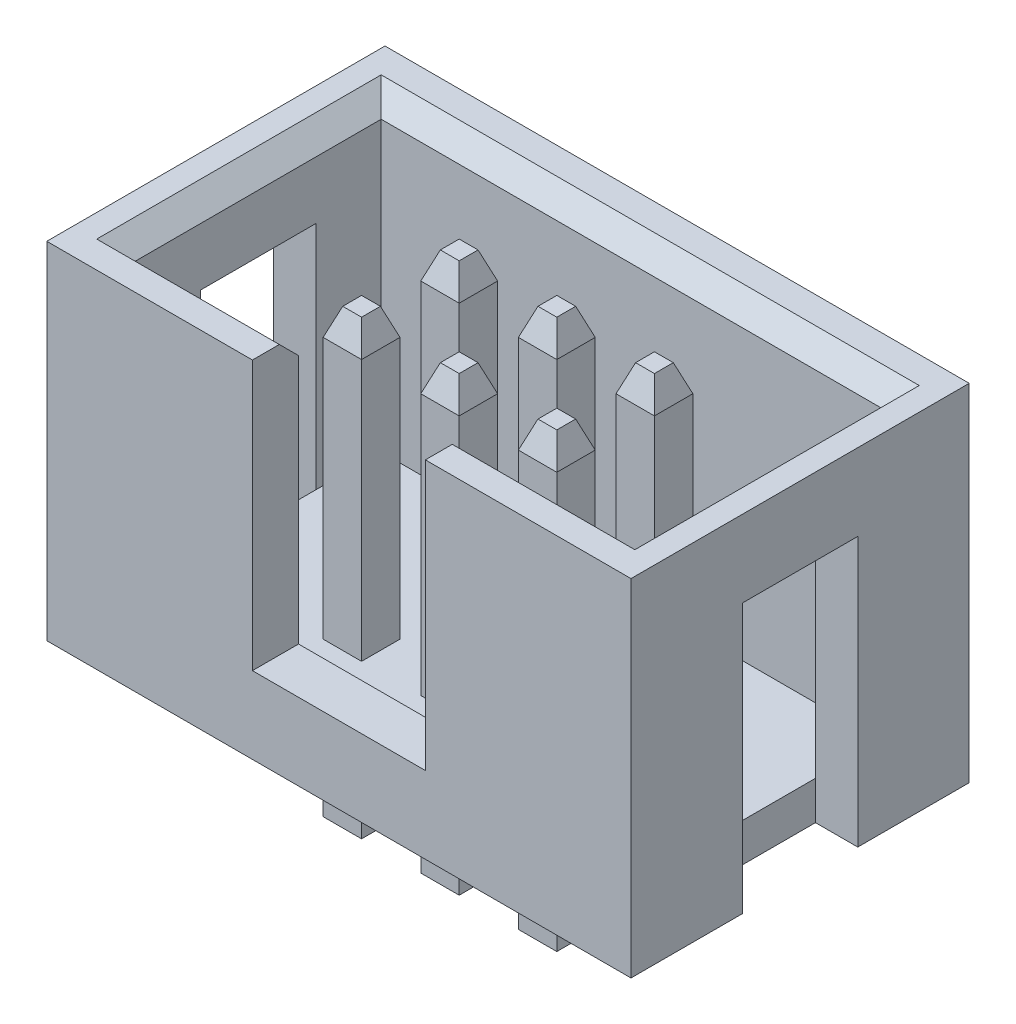
SolidWorks part; units mm, degrees
ref_plane "Front" through (0, 0, 0) normal (0, 0, 1) x (1, 0, 0)
ref_plane "Top" through (0, 0, 0) normal (0, 1, 0) x (1, 0, 0)
ref_plane "Right" through (0, 0, 0) normal (1, 0, 0) x (0, 0, -1)
sketch "Sketch1" plane through (0, 0, 0) normal (0, 1, 0) x (1, 0, 0)
  line L1 (0, 0) -> (15.2, 0)
  line L2 (0, 0) -> (0, 8.8)
  line L3 (0, 8.8) -> (15.2, 8.8)
  line L4 (15.2, 0) -> (15.2, 8.8)
  dimension "D1" = 15.2
  dimension "D2" = 8.8
extrude "Boss-Extrude1" add sketch "Sketch1" along normal blind 9
sketch "Sketch3" plane through (0, 9, 0) normal (0, 1, 0) x (1, 0, 0)
  line L0 (15.2, 8.8) -> (0, 8.8) construction
  line L1 (1.1, 7.6) -> (14.1, 7.6)
  line L2 (1.1, 7.6) -> (1.1, 1.2)
  line L3 (1.1, 1.2) -> (14.1, 1.2)
  line L4 (14.1, 7.6) -> (14.1, 1.2)
  line L5 (0, 8.8) -> (0, 0) construction
  dimension "D1" = 13
  dimension "D2" = 6.4
  dimension "D3" = 1.2
  dimension "D4" = 1.1
extrude "Cut-Extrude1" cut sketch "Sketch3" against normal blind 8
sketch "Sketch4" plane through (0, 9, 0) normal (0, 1, 0) x (1, 0, 0)
  line L0 (1.1, 1.2) -> (14.1, 1.2) construction
  line L1 (5.35, 1.2) -> (9.85, 1.2)
  line L2 (5.35, 1.2) -> (5.35, 0)
  line L3 (5.35, 0) -> (9.85, 0)
  line L4 (9.85, 1.2) -> (9.85, 0)
  line L5 (0, 0) -> (15.2, 0) construction
  line L6 (0, 8.8) -> (0, 0) construction
  dimension "D1" = 4.5
  dimension "D2" = 5.35
extrude "Cut-Extrude2" cut sketch "Sketch4" against normal blind 7
sketch "Sketch5" plane through (0, 0, 0) normal (-1, 0, 0) x (0, 0, 1)
  line L0 (-8.8, 0) -> (0, 0) construction
  line L1 (-5.9, 0) -> (-2.9, 0)
  line L2 (-5.9, 0) -> (-5.9, 7)
  line L3 (-5.9, 7) -> (-2.9, 7)
  line L4 (-2.9, 0) -> (-2.9, 7)
  line L5 (0, 9) -> (0, 0) construction
  dimension "D1" = 3
  dimension "D2" = 2.9
  dimension "D3" = 7
extrude "Cut-Extrude3" cut sketch "Sketch5" against normal blind 1.1
sketch "Sketch6" plane through (15.2, 0, 0) normal (1, 0, 0) x (0, 0, -1)
  line L0 (0, 0) -> (8.8, 0) construction
  line L1 (2.9, 0) -> (5.9, 0)
  line L2 (2.9, 0) -> (2.9, 7)
  line L3 (2.9, 7) -> (5.9, 7)
  line L4 (5.9, 0) -> (5.9, 7)
  line L5 (8.8, 9) -> (8.8, 0) construction
  dimension "D1" = 3
  dimension "D2" = 2.9
  dimension "D3" = 7
extrude "Cut-Extrude4" cut sketch "Sketch6" against normal blind 1.1
sketch "Sketch7" plane through (0, 1, 0) normal (0, 1, 0) x (1, 0, 0)
  line L0 (7.1, 6.17) -> (8.1, 6.17)
  line L1 (4.56, 6.17) -> (5.56, 6.17)
  line L2 (4.56, 6.17) -> (4.56, 5.17)
  line L3 (4.56, 5.17) -> (5.56, 5.17)
  line L4 (5.56, 6.17) -> (5.56, 5.17)
  line L5 (7.1, 6.17) -> (7.1, 5.17)
  line L6 (7.1, 5.17) -> (8.1, 5.17)
  line L7 (8.1, 6.17) -> (8.1, 5.17)
  line L8 (9.64, 6.17) -> (10.64, 6.17)
  line L9 (9.64, 6.17) -> (9.64, 5.17)
  line L10 (9.64, 5.17) -> (10.64, 5.17)
  line L11 (10.64, 6.17) -> (10.64, 5.17)
  line L12 (7.1, 3.63) -> (8.1, 3.63)
  line L13 (7.1, 3.63) -> (7.1, 2.63)
  line L14 (7.1, 2.63) -> (8.1, 2.63)
  line L15 (8.1, 3.63) -> (8.1, 2.63)
  line L16 (9.64, 3.63) -> (10.64, 3.63)
  line L17 (9.64, 3.63) -> (9.64, 2.63)
  line L18 (9.64, 2.63) -> (10.64, 2.63)
  line L19 (10.64, 3.63) -> (10.64, 2.63)
  line L20 (4.56, 3.63) -> (5.56, 3.63)
  line L21 (4.56, 3.63) -> (4.56, 2.63)
  line L22 (4.56, 2.63) -> (5.56, 2.63)
  line L23 (5.56, 3.63) -> (5.56, 2.63)
  line L24 (1.1, 5.9) -> (1.1, 2.9) construction
  line L25 (14.1, 7.6) -> (1.1, 7.6) construction
  dimension "D1" = 1
  dimension "D2" = 1
  dimension "D5" = 3.46
  dimension "D6" = 1.43
  dimension "D3" = 3
  dimension "D4" = 2
extrude "Boss-Extrude2" add sketch "Sketch7" along normal blind 7.5 and the other way blind 4
chamfer "Chamfer1" distance 0.7 angle 20 24 edges at (5.06, 8.5, -6.17) (5.56, 8.5, -5.67) (5.06, 8.5, -5.17) (4.56, 8.5, -5.67) (7.6, 8.5, -3.63) (8.1, 8.5, -3.13) (7.6, 8.5, -2.63) (7.1, 8.5, -3.13) (7.6, 8.5, -6.17) (8.1, 8.5, -5.67) (7.6, 8.5, -5.17) (7.1, 8.5, -5.67) (10.14, 8.5, -6.17) (10.64, 8.5, -5.67) (10.14, 8.5, -5.17) (9.64, 8.5, -5.67) (10.14, 8.5, -3.63) (10.64, 8.5, -3.13) (10.14, 8.5, -2.63) (9.64, 8.5, -3.13) (5.06, 8.5, -3.63) (5.56, 8.5, -3.13) (5.06, 8.5, -2.63) (4.56, 8.5, -3.13)
chamfer "Chamfer2" distance 0.5 angle 45 5 edges at (3.225, 9, -1.2) (1.1, 9, -4.4) (11.975, 9, -1.2) (14.1, 9, -4.4) (7.6, 9, -7.6)
